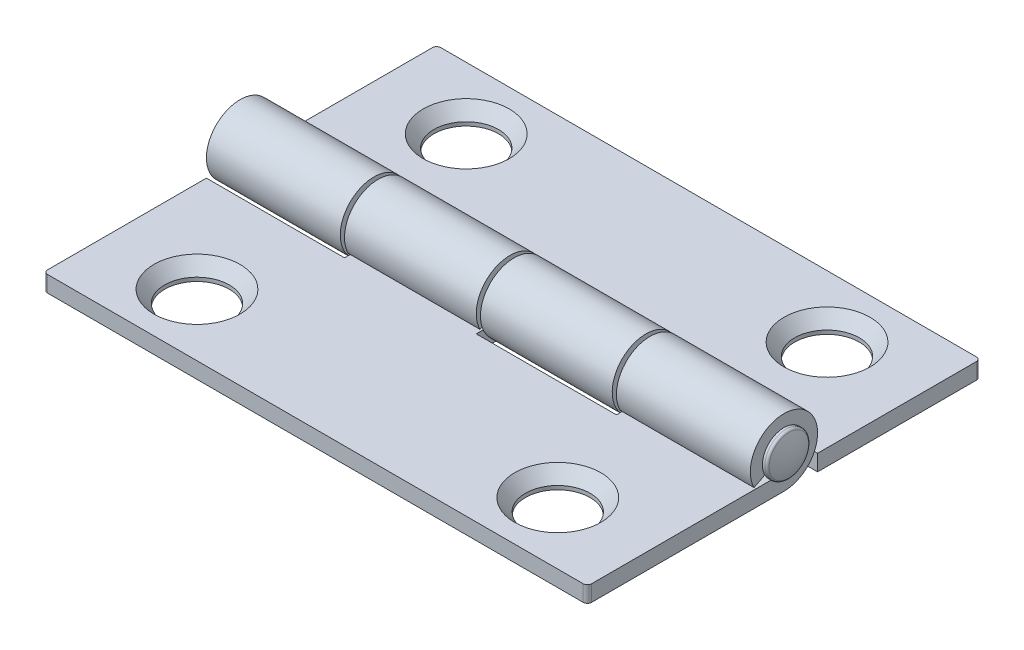
SolidWorks part; units mm, degrees
ref_plane "Front Plane" through (0, 0, 0) normal (0, 0, 1) x (1, 0, 0)
ref_plane "Top Plane" through (0, 0, 0) normal (0, 1, 0) x (1, 0, 0)
ref_plane "Right Plane" through (0, 0, 0) normal (1, 0, 0) x (0, 0, -1)
sketch "Sketch1" plane through (0, 0, 0) normal (0, 1, 0) x (1, 0, 0)
  line L0 (-25.654, 0) -> (25.654, 0) construction
  line L1 (-25.654, -18.542) -> (-25.654, 18.542) construction
  line L2 (17.018, 12.7) -> (17.018, -12.7) construction
  line L3 (-17.018, -18.542) -> (17.018, -18.542) construction
  line L4 (0, 0) -> (0, -18.542) construction
  line L5 (17.018, -9.652) -> (17.018, -15.748) construction
  line L7 (-17.018, 12.7) -> (17.018, 12.7) construction
  line L8 (-17.018, 12.7) -> (-17.018, -12.7) construction
  line L9 (-17.018, -12.7) -> (17.018, -12.7) construction
  line L10 (17.018, 12.7) -> (17.018, -12.7) construction
  line L11 (20.066, -12.7) -> (13.97, -12.7) construction
  line L12 (-17.018, 12.7) -> (17.018, -12.7) construction
  line L13 (-17.018, -12.7) -> (17.018, 12.7) construction
  circle A0 centre (17.018, -12.7) radius 4.064 construction
  point P4 (0, 0)
  point P8 (-25.654, 0)
  point P21 (17.018, -12.7)
  point P25 (17.018, 0)
  point P26 (17.018, -12.7)
  point P38 (17.018, -12.7)
  dimension "C'Sink Diameter" = 8.128
  dimension "Door Leaf Height" = 51.308
  dimension "Overall Width" = 37.084
  dimension "Hole Spacing" = 34.036
  dimension "Hole Diameter" = 6.096
  dimension "Hole Spacing 2" = 25.4
  dimension "Frame Leaf Height" = 51.308
  dimension "Door Leaf Width" = 18.542
  dimension "Frame Leaf Width" = 18.542
  dimension "Hole Offset" = 8.636
sketch "Sketch2" plane through (0, 0, 0) normal (1, 0, 0) x (0, 0, -1)
  line L2 (0, -3.175) -> (0, -1.651) construction
  line L4 (0, 1.651) -> (0, -1.651) construction
  circle A0 centre (0, 0) radius 3.175 construction
  circle A1 centre (0, 0) radius 2.032 construction
  point P8 (0, 0)
  dimension "Leaf OD" = 6.35
  dimension "Pin Head Diameter" = 4.064
  dimension "Leaf Thickness" = 1.524
  dimension "Pin Diameter" = 3.302
sketch "Sketch3" plane through (0, 0, 0) normal (1, 0, 0) x (0, 0, -1)
  line L3 (0, 0) -> (-3.175, -1.651) construction
  line L4 (0, -3.175) -> (-18.542, -3.175)
  line L5 (-18.542, -3.175) -> (-18.542, -1.651)
  line L7 (-18.542, -1.651) -> (0, -1.651)
  line L8 (-18.542, 0) -> (18.542, 0) construction
  line L9 (-1.4648, -0.7617) -> (-2.8169, -1.4648)
  line L11 (-3.175, 0) -> (-3.175, -1.651) construction
  circle A4 centre (0, 0) radius 1.651 construction
  circle A5 centre (0, 0) radius 3.175 construction
  arc A8 (-1.4648, -0.7617) -> (0, -1.651) centre (0, 0) cw
  arc A9 (-2.8169, -1.4648) -> (0, -3.175) centre (0, 0) cw
  point P0 (-2.8169, -1.4648)
  point P13 (-1.4648, -0.7617)
extrude "Boss-Extrude1" add sketch "Sketch3" along normal mid plane 51.308
sketch "Sketch4" plane through (0, 0, 0) normal (0, 1, 0) x (1, 0, 0)
  line L0 (-25.654, -3.175) -> (25.654, -3.175) construction
  line L1 (-25.654, -3.175) -> (25.654, -3.175) construction
  line L2 (25.654, 3.175) -> (-25.654, 3.175) construction
  line L3 (25.654, 3.175) -> (-25.654, 3.175) construction
  line L4 (0, -3.175) -> (0, 3.175)
  line L6 (0, 3.175) -> (12.827, 3.175)
  line L7 (12.827, -3.175) -> (0, -3.175)
  line L8 (12.827, 3.175) -> (12.827, -3.175)
  dimension "D1" = 12.827
extrude "Cut-Extrude1" cut sketch "Sketch4" against normal through all both and the other way through all
pattern_linear "LPattern1" count 2 spacing 25.654 along (-1, 0, 0) of "Cut-Extrude1"
sketch "Sketch5" plane through (0, -1.651, 0) normal (0, 1, 0) x (1, 0, 0)
  line L0 (-12.827, -3.175) -> (0, -3.175) construction
  line L1 (-12.827, 3.175) -> (-12.6286, 3.175)
  line L2 (-12.827, 3.175) -> (-12.827, -3.175)
  line L3 (-12.827, -3.175) -> (-12.6286, -3.175)
  line L4 (-12.6286, 3.175) -> (-12.6286, -3.175)
  line L5 (12.827, 3.175) -> (12.827, -3.175) construction
  line L6 (0, 3.175) -> (-0.1984, 3.175)
  line L7 (0, 3.175) -> (0, -3.175)
  line L8 (0, -3.175) -> (-0.1984, -3.175)
  line L9 (-0.1984, 3.175) -> (-0.1984, -3.175)
  line L10 (12.827, 3.175) -> (13.0254, 3.175)
  line L11 (12.827, 3.175) -> (12.827, -3.175)
  line L12 (12.827, -3.175) -> (13.0254, -3.175)
  line L13 (13.0254, 3.175) -> (13.0254, -3.175)
  line L14 (12.827, -3.175) -> (25.654, -3.175) construction
  line L15 (25.654, 3.175) -> (12.827, 3.175) construction
  dimension "D1" = 0.1984
extrude "Cut-Extrude2" cut sketch "Sketch5" against normal through all both and the other way through all
sketch "Sketch6" plane through (0, -1.651, 0) normal (0, 1, 0) x (1, 0, 0)
  line L0 (17.018, -12.7) -> (-17.018, -12.7) construction
  line L1 (17.018, -12.7) -> (17.018, -18.542) construction
  line L2 (-17.018, -12.7) -> (-17.018, -18.542) construction
  line L3 (17.018, -12.7) -> (18.542, -15.3396) construction
  circle A0 centre (17.018, -12.7) radius 3.048
  circle A3 centre (-17.018, -12.7) radius 3.048
  point P7 (18.542, -15.3396)
  dimension "D1" = 30
extrude "Cut-Extrude3" cut sketch "Sketch6" against normal through all
sketch "Sketch7" plane through (0, -1.651, 0) normal (0, 1, 0) x (1, 0, 0)
  circle A0 centre (-17.018, -12.7) radius 4.064
  circle A1 centre (17.018, -12.7) radius 4.064
  circle A2 centre (17.018, -12.7) radius 4.064 construction
extrude "Cut-Extrude4" cut sketch "Sketch7" against normal through all draft 41
fillet "Fillet1" radius 0.3969 2 edges at (25.654, -2.413, 18.542) (-25.654, -2.413, 18.542)
pattern_circular "CirPattern1" count 2 over 360 about axis through (0, 0, 0) along (0, 1, 0) of bodies 111 107
sketch "Sketch8" plane through (0, 0, 0) normal (1, 0, 0) x (0, 0, -1)
  circle A0 centre (0, 0) radius 1.651
  dimension "D1" = 3.302
extrude "Boss-Extrude2" add sketch "Sketch8" along normal mid plane 51.308 separate body
sketch "Sketch9" plane through (0, 0, 0) normal (0, 0, 1) x (1, 0, 0)
  line L2 (25.654, 2.032) -> (25.654, -2.032) construction
  line L3 (25.654, 0) -> (26.4477, 0) construction
  line L4 (0, -2.032) -> (0, 2.032) construction
  line L7 (25.654, 2.032) -> (25.654, 0)
  line L8 (25.654, 0) -> (26.4477, 0)
  line L9 (25.654, -1.651) -> (25.654, -3.175) construction
  line L10 (0, -2.032) -> (0, 2.032) construction
  line L11 (-25.654, 1.651) -> (-25.654, 3.175) construction
  line L12 (25.654, 2.032) -> (25.8769, 2.032)
  line L13 (25.654, 1.651) -> (25.654, 3.175) construction
  line L14 (-25.654, 0) -> (-26.4477, 0) construction
  line L15 (-25.654, 2.032) -> (-25.8769, 2.032)
  line L16 (-25.654, 0) -> (-26.4477, 0)
  line L17 (-25.654, 2.032) -> (-25.654, 0)
  line L21 (25.654, 1.651) -> (13.0254, 1.651) construction
  line L22 (25.654, 3.175) -> (13.0254, 3.175) construction
  line L24 (25.654, 0) -> (-25.654, 0) construction
  arc A0 (25.654, 2.032) -> (25.654, -2.032) centre (23.4499, 0) cw construction
  arc A4 (26.1152, 1.8658) -> (26.4477, 0) centre (21.0474, 0) cw
  arc A5 (25.8769, 2.032) -> (26.1152, 1.8658) centre (25.8769, 1.778) cw
  arc A8 (-25.8769, 2.032) -> (-26.1152, 1.8658) centre (-25.8769, 1.778) ccw
  arc A9 (-26.1152, 1.8658) -> (-26.4477, 0) centre (-21.0474, 0) ccw
  point P12 (25.654, 0)
  point P20 (26.0509, 0)
  point P29 (26.0509, 2.032)
  point P36 (25.654, 2.413)
  point P41 (-25.654, 2.413)
  point P42 (-26.0509, 2.032)
  point P43 (-26.0509, 0)
  dimension "D2" = 0.254
  dimension "D1" = 0.7937
revolve "Revolve1" add sketch "Sketch9" angle 360 about L24
equation "\"D1@Boss-Extrude1\" = \"Door Leaf Height@Sketch1\""
equation "\"D1@Sketch4\"=\"Door Leaf Height@Sketch1\" / 4"
equation "\"D3@LPattern1\"= \"D1@Sketch4\" * 2"
equation "\"D1@Sketch8\" = \"Pin Diameter@Sketch2\""
equation "\"D1@Boss-Extrude2\" = \"Door Leaf Height@Sketch1\""
